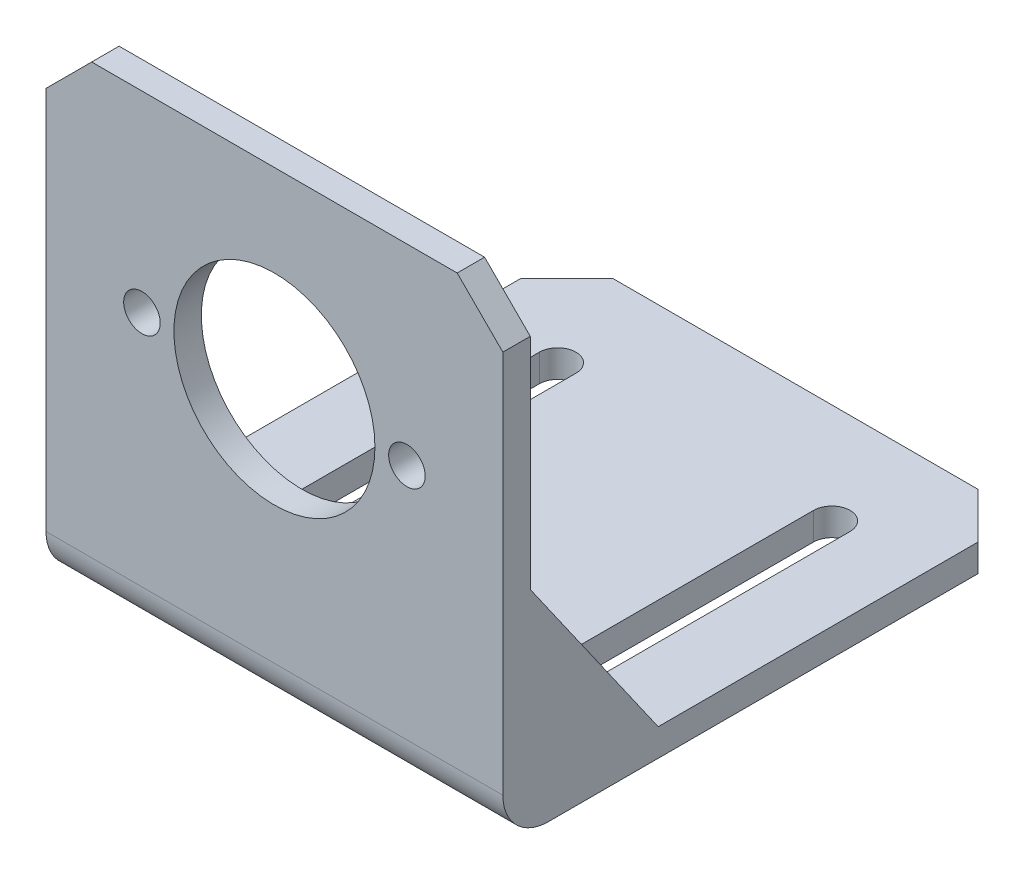
SolidWorks part; units mm, degrees
ref_plane "前基準面" through (0, 0, 0) normal (0, 0, 1) x (1, 0, 0)
ref_plane "上基準面" through (0, 0, 0) normal (0, 1, 0) x (1, 0, 0)
ref_plane "右基準面" through (0, 0, 0) normal (1, 0, 0) x (0, 0, -1)
sketch "草圖1" plane through (0, 0, 0) normal (0, 0, 1) x (1, 0, 0)
  line L1 (-25, 26) -> (25, 26)
  line L2 (-25, 26) -> (-25, -26)
  line L3 (-25, -26) -> (25, -26)
  line L4 (25, 26) -> (25, -26)
  point P4 (0, 26)
  point P6 (-25, 0)
  dimension "D1" = 50
  dimension "D2" = 52
extrude "填料-伸長1" add sketch "草圖1" along normal blind 3
sketch "草圖2" plane through (0, 0, 0) normal (0, 0, -1) x (-1, 0, 0)
  line L0 (25, 26) -> (25, -26) construction
  line L1 (-25, -26) -> (25, -26)
  line L2 (-25, -26) -> (-25, -23)
  line L3 (-25, -23) -> (25, -23)
  line L4 (25, -26) -> (25, -23)
  dimension "D1" = 3
extrude "填料-伸長2" add sketch "草圖2" along normal blind 54
sketch "草圖3" plane through (0, 0, 3) normal (0, 0, 1) x (1, 0, 0)
  line L0 (25, 26) -> (-25, 26) construction
  line L1 (0, 16) -> (0, -6) construction
  circle A0 centre (0, 5) radius 11
  circle A1 centre (14.5, 5) radius 2
  circle A2 centre (-14.5, 5) radius 2
  dimension "D1" = 22
  dimension "D3" = 4
  dimension "D2" = 21
  dimension "D4" = 14.5
extrude "除料-伸長1" cut sketch "草圖3" against normal through all
chamfer "導角1" distance 5 angle 45 2 edges at (-25, 26, 1.5) (25, 26, 1.5)
chamfer "導角2" distance 5 angle 45 2 edges at (-25, -24.5, -54) (25, -24.5, -54)
sketch "草圖4" plane through (0, -26, 0) normal (0, -1, 0) x (1, 0, 0)
  line L0 (15, -43) -> (15, -13) construction
  line L1 (13, -43) -> (13, -13)
  line L2 (17, -43) -> (17, -13)
  line L3 (0, 3) -> (0, -54) construction
  line L4 (-25, 3) -> (25, 3) construction
  line L5 (20, -54) -> (-20, -54) construction
  line L6 (25, 3) -> (25, -49) construction
  line L7 (-15, -43) -> (-15, -13) construction
  line L8 (-13, -43) -> (-13, -13)
  line L9 (-17, -43) -> (-17, -13)
  arc A0 (13, -43) -> (17, -43) centre (15, -43) ccw
  arc A1 (17, -13) -> (13, -13) centre (15, -13) ccw
  arc A2 (-13, -43) -> (-17, -43) centre (-15, -43) cw
  arc A3 (-17, -13) -> (-13, -13) centre (-15, -13) cw
  point P2 (15, -28)
  point P17 (-15, -28)
  dimension "D1" = 4
  dimension "D2" = 11
  dimension "D3" = 30
  dimension "D4" = 10
  dimension "D5" = 15
  dimension "D6" = 30
extrude "除料-伸長2" cut sketch "草圖4" against normal through all
sketch "草圖5" plane through (25, 0, 0) normal (1, 0, 0) x (0, 0, -1)
  line L0 (0, -23) -> (0, -3)
  line L1 (0, -23) -> (0, 21) construction
  line L2 (0, -3) -> (14, -23)
  line L3 (49, -23) -> (0, -23) construction
  line L4 (14, -23) -> (0, -23)
  dimension "D1" = 20
  dimension "D2" = 14
extrude "填料-伸長3" add sketch "草圖5" against normal up to surface (50 mm away)
sketch "草圖6" plane through (25, 0, 0) normal (1, 0, 0) x (0, 0, -1)
  line L0 (0, -3) -> (14, -23)
  line L1 (14, -23) -> (0, -23)
  line L2 (0, -23) -> (0, -3)
extrude "除料-伸長3" cut sketch "草圖6" against normal blind 44 from offset 3 offset against normal yes
fillet "圓角1" radius 5 1 edges at (0, -26, 3)
